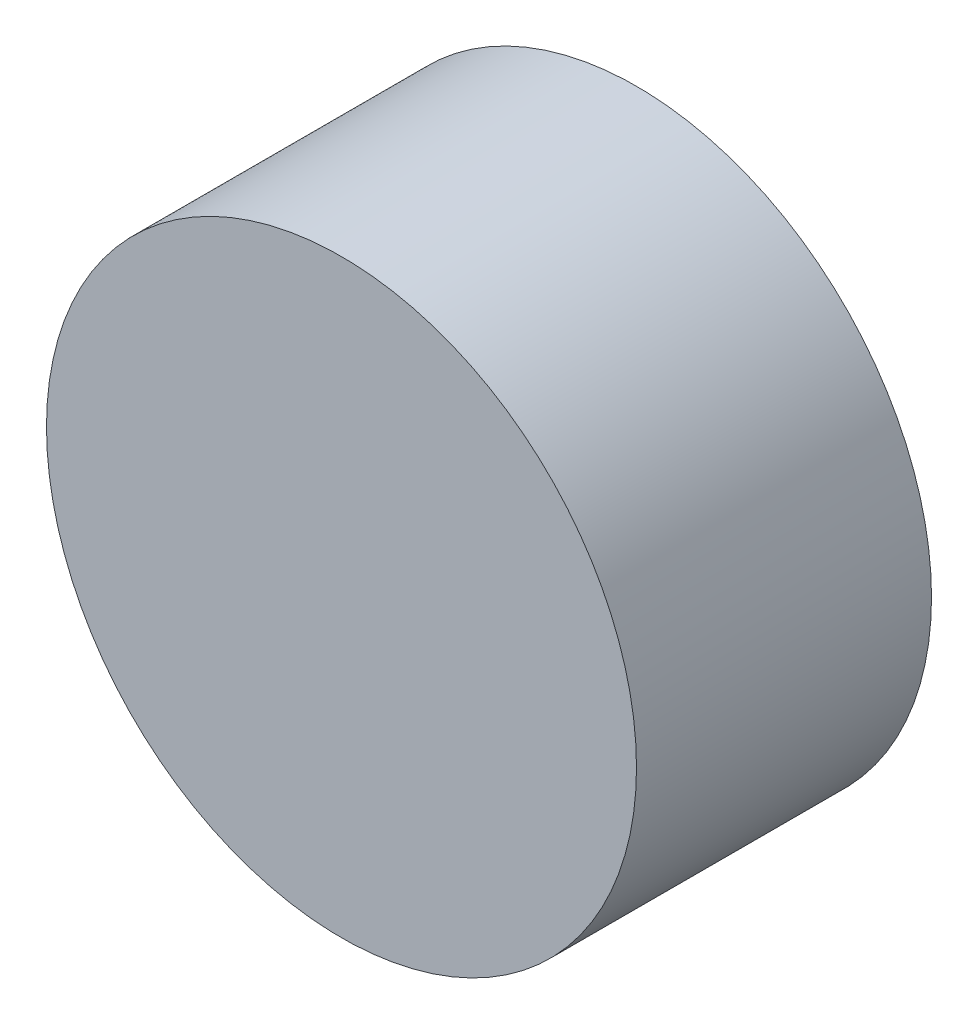
SolidWorks part; units mm, degrees
ref_plane "Front Plane" through (0, 0, 0) normal (0, 0, 1) x (1, 0, 0)
ref_plane "Top Plane" through (0, 0, 0) normal (0, 1, 0) x (1, 0, 0)
ref_plane "Right Plane" through (0, 0, 0) normal (1, 0, 0) x (0, 0, -1)
sketch "Sketch1" plane through (0, 0, 0) normal (0, 0, 1) x (1, 0, 0)
  circle A0 centre (0, 0) radius 100
  dimension "D1" = 200
extrude "Boss-Extrude1" add sketch "Sketch1" along normal blind 100
sketch "Sketch2" plane through (0, 0, 0) normal (0, 0, -1) x (-1, 0, 0)
  line L1 (-12.5, -5) -> (12.5, -5)
  line L2 (-12.5, -5) -> (-12.5, 5)
  line L3 (-12.5, 5) -> (12.5, 5)
  line L4 (12.5, -5) -> (12.5, 5)
  line L5 (-12.5, -5) -> (12.5, 5) construction
  line L6 (-12.5, 5) -> (12.5, -5) construction
  point P0 (0, 0)
  dimension "D1" = 25
  dimension "D2" = 10
extrude "Boss-Extrude2" add sketch "Sketch2" along normal blind 20 and the other way blind 20
sketch "Sketch4" plane through (0, -5, 0) normal (0, -1, 0) x (1, 0, 0)
  circle A0 centre (0, -10) radius 5
  dimension "D1" = 10
extrude "Cut-Extrude1" cut sketch "Sketch4" against normal blind 20
sketch "Sketch6" plane through (0, 0, 0) normal (1, 0, 0) x (0, 0, -1)
  line L0 (0, 0) -> (-100, 0) construction
  point P1 (0, 0)
ref_plane "Plane1" through (0, 0, -10) normal (0, 0, 1) x (1, 0, 0)
sketch "Sketch7" plane through (0, 0, -10) normal (0, 0, 1) x (1, 0, 0)
  line L0 (174.8845, 0) -> (-174.8845, 0) construction
  line L1 (0, -105.1425) -> (0, 105.1425) construction
  point P4 (0, 0)
  point P8 (0, 0)
